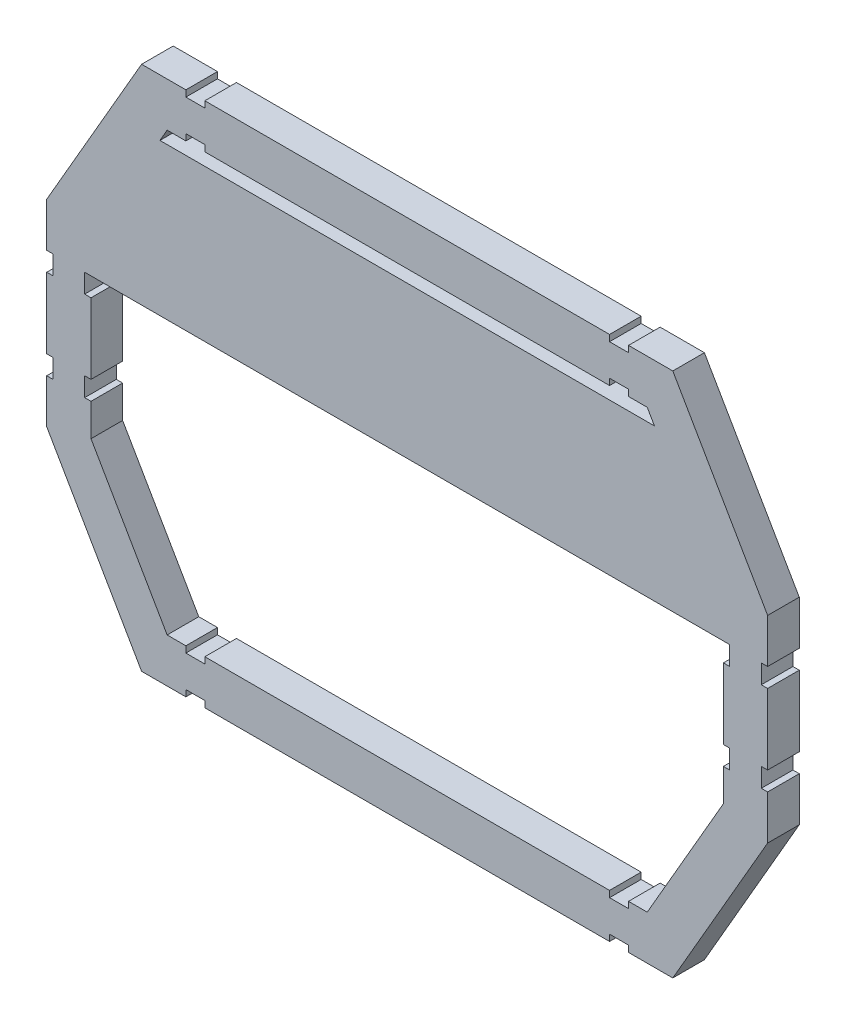
SolidWorks part; units mm, degrees
ref_plane "Plan de face" through (0, 0, 0) normal (0, 0, 1) x (1, 0, 0)
ref_plane "Plan de dessus" through (0, 0, 0) normal (0, 1, 0) x (1, 0, 0)
ref_plane "Plan de droite" through (0, 0, 0) normal (1, 0, 0) x (0, 0, -1)
sketch "Esquisse1" plane through (0, 0, 0) normal (0, 0, 1) x (1, 0, 0)
  line L0 (82.5398, -153.6268) -> (18.5398, -153.6268)
  line L1 (18.5398, -153.6268) -> (18.5398, -152.6268)
  line L2 (18.5398, -152.6268) -> (15.5398, -152.6268)
  line L3 (15.5398, -152.6268) -> (15.5398, -153.6268)
  line L4 (15.5398, -153.6268) -> (8.5398, -153.6268)
  line L5 (8.5398, -153.6268) -> (-6.4602, -127.646)
  line L6 (-6.4602, -127.646) -> (-6.4602, -120.646)
  line L7 (-6.4602, -120.646) -> (-5.4602, -120.646)
  line L8 (-5.4602, -120.646) -> (-5.4602, -117.646)
  line L9 (-5.4602, -117.646) -> (-6.4602, -117.646)
  line L10 (-6.4602, -117.646) -> (-6.4602, -106.4691)
  line L11 (50.5398, -153.6268) -> (50.5398, -70.4883) construction
  line L12 (100.5398, -112.0576) -> (0.5398, -112.0576) construction
  line L13 (1.0398, -140.6364) -> (50.5398, -112.0576) construction
  line L14 (0.5398, -106.4691) -> (0.5398, -117.646)
  line L15 (0.5398, -117.646) -> (-0.4602, -117.646)
  line L16 (-0.4602, -117.646) -> (-0.4602, -120.646)
  line L17 (-0.4602, -120.646) -> (0.5398, -120.646)
  line L18 (0.5398, -120.646) -> (0.5398, -125.7704)
  line L19 (0.5398, -125.7704) -> (12.5813, -146.6268)
  line L20 (12.5813, -146.6268) -> (15.5398, -146.6268)
  line L21 (15.5398, -146.6268) -> (15.5398, -147.6268)
  line L22 (15.5398, -147.6268) -> (18.5398, -147.6268)
  line L23 (18.5398, -147.6268) -> (18.5398, -146.6268)
  line L24 (18.5398, -146.6268) -> (82.5398, -146.6268)
  line L25 (1.0398, -83.4787) -> (50.5398, -112.0576) construction
  line L26 (18.5398, -77.4883) -> (82.5398, -77.4883)
  line L27 (18.5398, -76.4883) -> (18.5398, -77.4883)
  line L28 (15.5398, -76.4883) -> (18.5398, -76.4883)
  line L29 (15.5398, -77.4883) -> (15.5398, -76.4883)
  line L30 (12.5813, -77.4883) -> (15.5398, -77.4883)
  line L31 (88.4984, -77.4883) -> (89.642, -79.4691)
  line L33 (-0.4602, -103.4691) -> (0.5398, -103.4691)
  line L34 (-0.4602, -106.4691) -> (-0.4602, -103.4691)
  line L35 (0.5398, -106.4691) -> (-0.4602, -106.4691)
  line L36 (-5.4602, -106.4691) -> (-6.4602, -106.4691)
  line L37 (-5.4602, -103.4691) -> (-5.4602, -106.4691)
  line L38 (-6.4602, -103.4691) -> (-5.4602, -103.4691)
  line L39 (-6.4602, -96.4691) -> (-6.4602, -103.4691)
  line L40 (8.5398, -70.4883) -> (-6.4602, -96.4691)
  line L41 (15.5398, -70.4883) -> (8.5398, -70.4883)
  line L42 (15.5398, -71.4883) -> (15.5398, -70.4883)
  line L43 (18.5398, -71.4883) -> (15.5398, -71.4883)
  line L44 (18.5398, -70.4883) -> (18.5398, -71.4883)
  line L45 (82.5398, -70.4883) -> (18.5398, -70.4883)
  line L46 (100.0398, -83.4787) -> (50.5398, -112.0576) construction
  line L47 (100.0398, -140.6364) -> (50.5398, -112.0576) construction
  line L48 (82.5398, -70.4883) -> (82.5398, -71.4883)
  line L49 (82.5398, -71.4883) -> (85.5398, -71.4883)
  line L50 (85.5398, -71.4883) -> (85.5398, -70.4883)
  line L51 (85.5398, -70.4883) -> (92.5398, -70.4883)
  line L52 (92.5398, -70.4883) -> (107.5398, -96.4691)
  line L53 (107.5398, -96.4691) -> (107.5398, -103.4691)
  line L54 (107.5398, -103.4691) -> (106.5398, -103.4691)
  line L55 (106.5398, -103.4691) -> (106.5398, -106.4691)
  line L56 (106.5398, -106.4691) -> (107.5398, -106.4691)
  line L57 (100.5398, -106.4691) -> (101.5398, -106.4691)
  line L58 (101.5398, -106.4691) -> (101.5398, -103.4691)
  line L59 (101.5398, -103.4691) -> (100.5398, -103.4691)
  line L62 (88.4984, -77.4883) -> (85.5398, -77.4883)
  line L63 (85.5398, -77.4883) -> (85.5398, -76.4883)
  line L64 (85.5398, -76.4883) -> (82.5398, -76.4883)
  line L65 (82.5398, -76.4883) -> (82.5398, -77.4883)
  line L66 (82.5398, -147.6268) -> (82.5398, -146.6268)
  line L67 (85.5398, -147.6268) -> (82.5398, -147.6268)
  line L68 (85.5398, -146.6268) -> (85.5398, -147.6268)
  line L69 (88.4984, -146.6268) -> (85.5398, -146.6268)
  line L70 (100.5398, -125.7704) -> (88.4984, -146.6268)
  line L71 (100.5398, -120.646) -> (100.5398, -125.7704)
  line L72 (101.5398, -120.646) -> (100.5398, -120.646)
  line L73 (101.5398, -117.646) -> (101.5398, -120.646)
  line L74 (100.5398, -117.646) -> (101.5398, -117.646)
  line L75 (100.5398, -106.4691) -> (100.5398, -117.646)
  line L76 (107.5398, -117.646) -> (107.5398, -106.4691)
  line L77 (106.5398, -117.646) -> (107.5398, -117.646)
  line L78 (106.5398, -120.646) -> (106.5398, -117.646)
  line L79 (107.5398, -120.646) -> (106.5398, -120.646)
  line L80 (107.5398, -127.646) -> (107.5398, -120.646)
  line L81 (92.5398, -153.6268) -> (107.5398, -127.646)
  line L82 (85.5398, -153.6268) -> (92.5398, -153.6268)
  line L83 (85.5398, -152.6268) -> (85.5398, -153.6268)
  line L84 (82.5398, -152.6268) -> (85.5398, -152.6268)
  line L85 (82.5398, -153.6268) -> (82.5398, -152.6268)
  line L86 (0.5398, -103.4691) -> (100.5398, -103.4691)
  line L87 (11.4377, -79.4691) -> (89.642, -79.4691)
  line L88 (12.5813, -77.4883) -> (11.4377, -79.4691)
  point P10 (1.0398, -140.6364)
  point P41 (-6.4602, -112.0576)
  point P73 (50.5398, -77.4883)
  point P74 (50.5398, -146.6268)
  point P75 (50.5398, -146.6268)
  point P94 (107.5398, -112.0576)
  dimension "D1" = 1
  dimension "D2" = 3
  dimension "D3" = 7
  dimension "D4" = 3
  dimension "D5" = 7
  dimension "D6" = 60
  dimension "D7" = 90
  dimension "D8" = 1
  dimension "D9" = 1
  dimension "D10" = 1
  dimension "D11" = 7
  dimension "D12" = 7
  dimension "D13" = 7
  dimension "D14" = 30
  dimension "D15" = 35
  dimension "D16" = 24
extrude "Boss.-Extru.1" add sketch "Esquisse1" along normal blind 5
